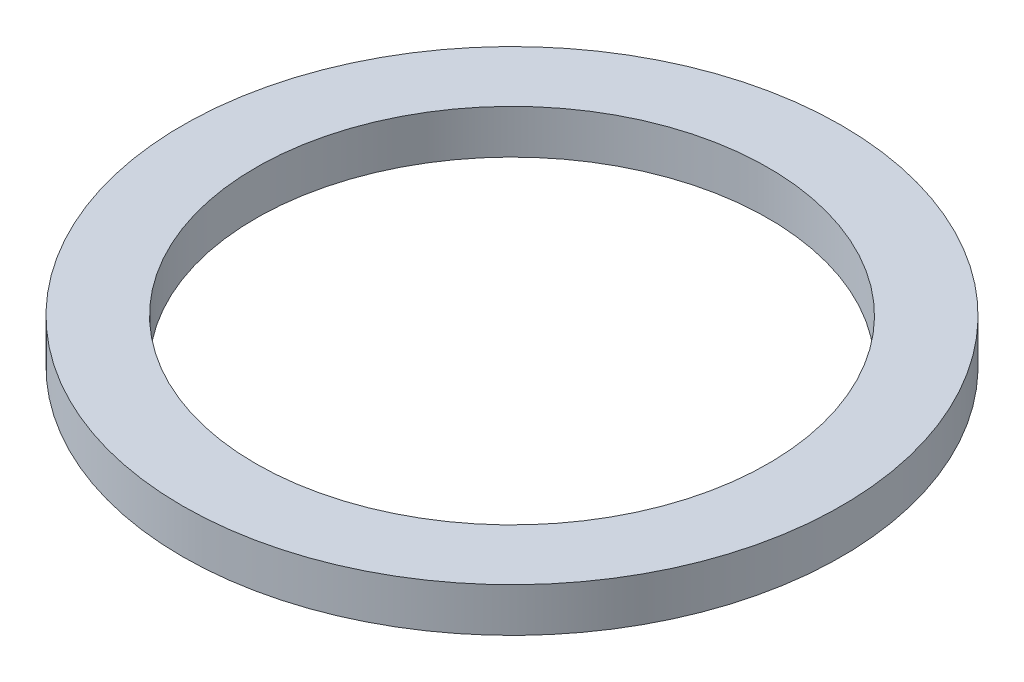
SolidWorks part; units mm, degrees
material "Teak"
ref_plane "Front Plane" through (0, 0, 0) normal (0, 0, 1) x (1, 0, 0)
ref_plane "Top Plane" through (0, 0, 0) normal (0, 1, 0) x (1, 0, 0)
ref_plane "Right Plane" through (0, 0, 0) normal (1, 0, 0) x (0, 0, -1)
sketch "Sketch2" plane through (0, 0, 0) normal (0, 1, 0) x (1, 0, 0)
  circle A0 centre (0, 0) radius 17.5
  circle A1 centre (0, 0) radius 22.5
  dimension "D1" = 35
  dimension "D2" = 45
extrude "Boss-Extrude1" add sketch "Sketch2" along normal blind 3
